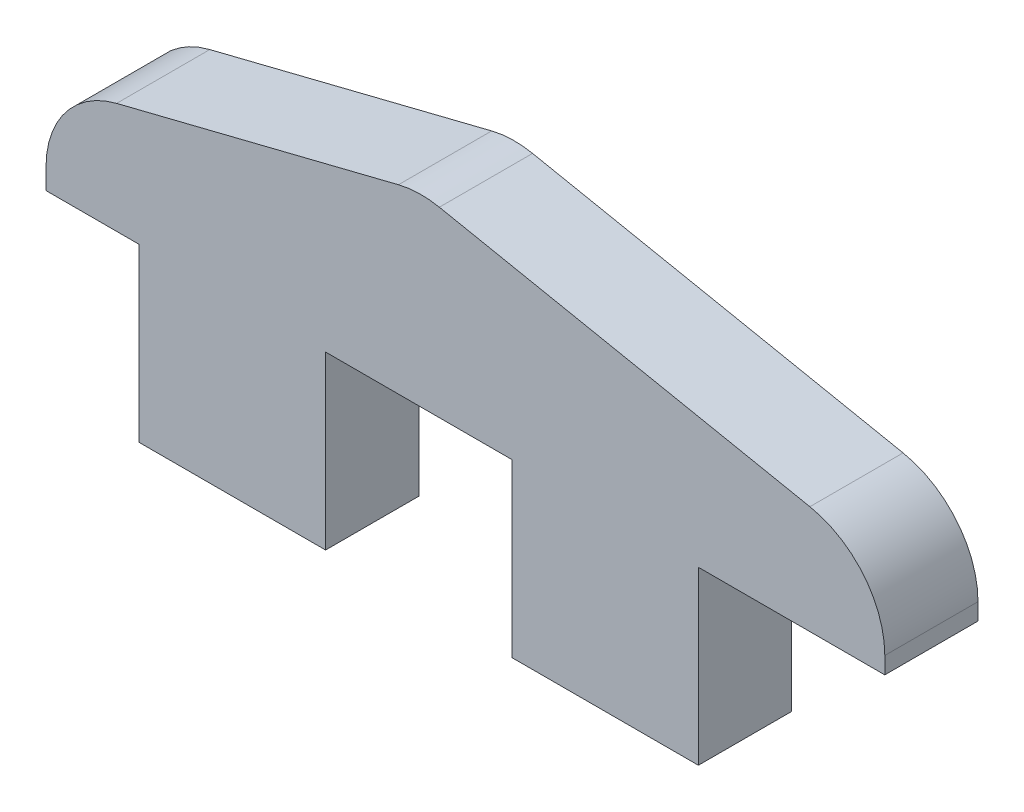
SolidWorks part; units mm, degrees
ref_plane "Front Plane" through (0, 0, 0) normal (0, 0, 1) x (1, 0, 0)
ref_plane "Top Plane" through (0, 0, 0) normal (0, 1, 0) x (1, 0, 0)
ref_plane "Right Plane" through (0, 0, 0) normal (1, 0, 0) x (0, 0, -1)
sketch "Sketch1" plane through (0, 0, 0) normal (0, 0, 1) x (1, 0, 0)
  line L0 (0, 5.842) -> (6.35, 5.842)
  line L1 (0, 0) -> (-6.35, 0)
  line L2 (0, 0) -> (0, 5.842)
  line L3 (3.175, 5.842) -> (3.175, 14.5694) construction
  line L4 (-6.35, 0) -> (-6.35, 5.842)
  line L5 (6.35, 0) -> (12.7, 0)
  line L6 (6.35, 0) -> (6.35, 5.842)
  line L8 (12.7, 0) -> (12.7, 5.842)
  line L10 (-6.35, 5.842) -> (-9.525, 5.842)
  line L11 (-9.525, 5.842) -> (-9.525, 9.017)
  line L12 (-9.525, 9.017) -> (3.175, 12.192)
  line L13 (12.7, 5.842) -> (19.05, 5.842)
  line L14 (19.05, 5.842) -> (19.05, 9.017)
  line L15 (19.05, 9.017) -> (3.175, 12.192)
  dimension "D1" = 5.842
  dimension "D2" = 5.842
  dimension "D3" = 6.35
  dimension "D4" = 6.35
  dimension "D5" = 6.35
  dimension "D6" = 3.175
  dimension "D7" = 3.175
extrude "Boss-Extrude1" add sketch "Sketch1" along normal blind 3.175
fillet "Fillet1" radius 3.175 3 edges at (3.175, 12.192, 1.5875) (-9.525, 9.017, 1.5875) (19.05, 9.017, 1.5875)
